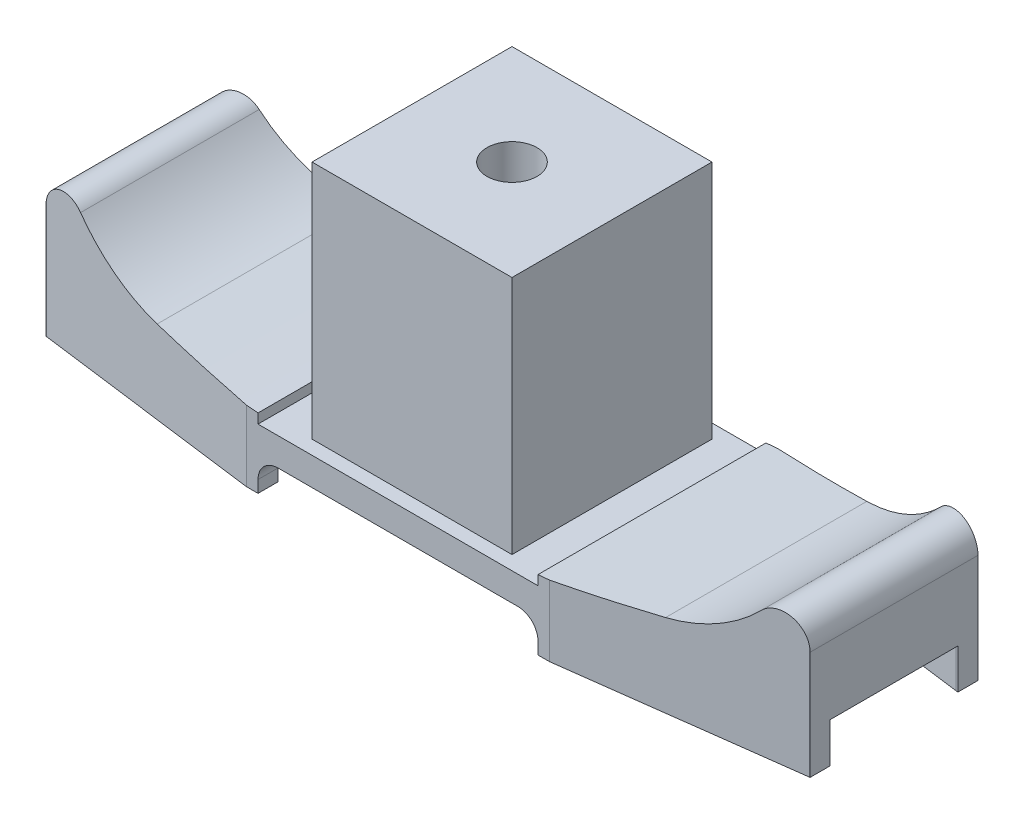
SolidWorks part; units mm, degrees
material "ABS"
ref_plane "Front Plane" through (0, 0, 0) normal (0, 0, 1) x (1, 0, 0)
ref_plane "Top Plane" through (0, 0, 0) normal (0, 1, 0) x (1, 0, 0)
ref_plane "Right Plane" through (0, 0, 0) normal (1, 0, 0) x (0, 0, -1)
sketch "Sketch1" plane through (0, 0, 0) normal (0, 1, 0) x (1, 0, 0)
  line L0 (-7.5767, 5.7) -> (-19.5345, 4.1659)
  line L1 (-7.5779, -5.7) -> (-19.0844, -4.1992)
  line L2 (7.5779, -5.7) -> (-7.5779, -5.7)
  line L3 (7.5779, -5.7) -> (19.0844, -4.1992)
  line L4 (7.5779, 5.7) -> (19.0844, 4.1992)
  line L5 (-15, 0) -> (15, 0) construction
  line L6 (15, 0) -> (19, 0) construction
  line L7 (0, 0) -> (0, 4.5) construction
  line L8 (22, 0) -> (22, 4.5) construction
  line L9 (-7.5, 4.5) -> (7.5, 4.5)
  line L10 (19, 0) -> (22, 0) construction
  line L11 (7.5, 4.5) -> (19, 3)
  line L12 (7.5, 4.5) -> (7.5, -4.5) construction
  line L13 (7.5, -4.5) -> (-7.5, -4.5)
  line L14 (7.5, -4.5) -> (19, -3)
  line L15 (-7.5, -4.5) -> (-19, -3)
  line L16 (-7.5, 4.5) -> (-7.5, -4.5) construction
  line L17 (-19, 0) -> (-22, 0) construction
  line L18 (-15, 0) -> (-19, 0) construction
  line L19 (-7.5, 4.5) -> (-19.3818, 2.9756)
  line L20 (-7.5767, 5.7) -> (7.5779, 5.7)
  line L21 (-7.513, -4.7) -> (-19.0132, -3.2)
  line L22 (-7.5128, 4.7) -> (-19.4072, 3.174)
  line L23 (-7.5128, 4.7) -> (7.513, 4.7)
  line L24 (7.513, 4.7) -> (19.0132, 3.2)
  line L25 (7.513, -4.7) -> (19.0132, -3.2)
  line L26 (7.513, -4.7) -> (-7.513, -4.7)
  circle A0 centre (19, 0) radius 1.5
  circle A1 centre (15, 0) radius 1.5
  arc A2 (19, -3) -> (19, 3) centre (19, 0) ccw
  circle A3 centre (9.5, 0) radius 2
  circle A4 centre (-9.5, 0) radius 2
  arc A5 (-19, -3) -> (-19.3818, 2.9756) centre (-19, 0) cw
  circle A6 centre (-15, 0) radius 1.5
  circle A7 centre (-19, 0) radius 1.5
  circle A8 centre (0, 0) radius 1.5
  arc A9 (-19.0844, -4.1992) -> (-19.5345, 4.1659) centre (-19, 0) cw
  arc A10 (19.0844, -4.1992) -> (19.0844, 4.1992) centre (19, 0) ccw
  arc A11 (-19.0132, -3.2) -> (-19.4072, 3.174) centre (-19, 0) cw
  arc A12 (19.0132, -3.2) -> (19.0132, 3.2) centre (19, 0) ccw
  point P25 (0, -4.5)
  dimension "D1" = 3
  dimension "D2" = 3
  dimension "D3" = 4
  dimension "D4" = 4
  dimension "D5" = 3
  dimension "D6" = 3
  dimension "D7" = 3
  dimension "D8" = 3
  dimension "D9" = 44
  dimension "D10" = 15
  dimension "D11" = 30
  dimension "D12" = 0.2
extrude "Boss-Extrude1" add sketch "Sketch1" along normal blind 2 contours L3 A10 L4 L20 L0 A9 L1 L2 L15 A5 L19 L9 L11 A2 L14 L13
sketch "Sketch2" plane through (0, 2, 0) normal (0, 1, 0) x (1, 0, 0)
  line L6 (7.5779, -5.7) -> (19.0844, -4.1992)
  line L7 (19.0844, 4.1992) -> (7.5779, 5.7)
  line L8 (7.5779, 5.7) -> (-7.5767, 5.7)
  line L9 (-7.5767, 5.7) -> (-19.5345, 4.1659)
  line L10 (-19.0844, -4.1992) -> (-7.5779, -5.7)
  line L11 (-7.5779, -5.7) -> (7.5779, -5.7)
  line L12 (7.5779, -5.7) -> (19.0844, -4.1992)
  line L13 (19.0844, 4.1992) -> (7.5779, 5.7)
  line L14 (7.5779, 5.7) -> (-7.5767, 5.7)
  line L15 (-7.5767, 5.7) -> (-19.5345, 4.1659)
  line L16 (-19.0844, -4.1992) -> (-7.5779, -5.7)
  line L17 (-7.5779, -5.7) -> (7.5779, -5.7)
  arc A2 (19.0844, -4.1992) -> (19.0844, 4.1992) centre (19, 0) ccw
  arc A3 (-19.5345, 4.1659) -> (-19.0844, -4.1992) centre (-19, 0) ccw
  arc A4 (19.0844, -4.1992) -> (19.0844, 4.1992) centre (19, 0) ccw
  arc A5 (-19.5345, 4.1659) -> (-19.0844, -4.1992) centre (-19, 0) ccw
  dimension "D1" = 0
extrude "Boss-Extrude2" add sketch "Sketch2" along normal blind 1
sketch "Sketch3" plane through (0, 3, 0) normal (0, 1, 0) x (1, 0, 0)
  line L0 (-5, 0) -> (-5, 5)
  line L1 (-5, 5) -> (5, 5)
  line L2 (5, 5) -> (5, -5)
  line L3 (5, -5) -> (-5, -5)
  line L4 (-5, -5) -> (-5, 0)
  circle A0 centre (0, 0) radius 5 construction
  dimension "D1" = 10
extrude "Boss-Extrude3" add sketch "Sketch3" along normal blind 12
sketch "Sketch4" plane through (0, 0, 5.7) normal (0, 0, 1) x (1, 0, 0)
  line L0 (-7.5779, 3) -> (7.5779, 3) construction
  line L1 (-7.5779, 3) -> (7.5779, 3)
  line L2 (-7, 4) -> (7, 4)
  line L3 (0, 0) -> (0, 89.2)
  line L4 (-10.4945, 18.9799) -> (-12.7116, 4.1446)
  line L5 (10.4945, 18.9799) -> (12.7116, 4.1446)
  line L6 (-19.103, 3) -> (-19.103, 11.5623)
  line L7 (-19.0844, 3) -> (-7.5779, 3) construction
  line L8 (19.103, 3) -> (19.103, 11.5623)
  line L9 (23.2, 3) -> (19.0844, 3) construction
  line L10 (-7, 3) -> (-7, 3.4854)
  line L11 (7, 3) -> (7, 3.4854)
  line L12 (-7, 3) -> (-19.103, 3)
  line L13 (-7.5779, 4) -> (7.5779, 4) construction
  line L14 (7.5779, 3) -> (19.103, 3)
  arc A0 (-12.7116, 4.1446) -> (12.7116, 4.1446) centre (0, 89.2) ccw
  circle A1 centre (0, 89.2) radius 71
  circle A2 centre (-11.603, 11.5623) radius 7.5
  circle A3 centre (11.603, 11.5623) radius 7.5
  arc A4 (19.103, 5.3485) -> (-19.103, 5.3485) centre (0, 89.2) ccw
  arc A5 (19.103, 5.421) -> (16.9496, 6.3026) centre (17.8459, 5.421) ccw
  arc A6 (-17.1173, 6.4787) -> (-19.103, 5.7031) centre (-17.9587, 5.7031) ccw
  arc A7 (-18.9592, 13.0239) -> (18.9592, 13.0239) centre (0, 89.2) ccw
  point P36 (0, 10.7)
  dimension "D2" = 172
  dimension "D5" = 142
  dimension "D8" = 78.5
  dimension "D3" = 8.5
  dimension "D4" = 8.5
  dimension "D6" = 7
  dimension "D7" = 7
  dimension "D9" = 7.7
  dimension "D1" = 1
extrude "Boss-Extrude4" add sketch "Sketch4" against normal up to surface (11.4 mm away)
sketch "Sketch5" plane through (0, 3, 0) normal (0, -1, 0) x (1, 0, 0)
  line L1 (19.103, 4.1987) -> (19.103, -4.1987)
  line L2 (-19.103, -4.2212) -> (-19.103, 4.1987)
  line L3 (-19.0844, 4.1992) -> (-7.5779, 5.7)
  line L4 (-7.5779, 5.7) -> (-19.103, 5.7)
  line L5 (-19.103, 5.7) -> (-19.103, 4.1987)
  line L6 (-19.0844, 4.1992) -> (-7.5779, 5.7)
  line L7 (-7.5779, 5.7) -> (-19.103, 5.7)
  line L8 (-19.103, 5.7) -> (-19.103, 4.1987)
  line L9 (19.103, 5.7) -> (7.5779, 5.7)
  line L10 (7.5779, 5.7) -> (19.0844, 4.1992)
  line L11 (19.103, 4.1987) -> (19.103, 5.7)
  line L12 (19.103, 5.7) -> (7.5779, 5.7)
  line L13 (7.5779, 5.7) -> (19.0844, 4.1992)
  line L14 (19.103, 4.1987) -> (19.103, 5.7)
  line L15 (-19.103, -5.7) -> (-7.5767, -5.7)
  line L16 (-7.5767, -5.7) -> (-19.103, -4.2212)
  line L17 (-19.103, -4.2212) -> (-19.103, -5.7)
  line L18 (-19.103, -5.7) -> (-7.5767, -5.7)
  line L19 (-7.5767, -5.7) -> (-19.103, -4.2212)
  line L20 (-19.103, -4.2212) -> (-19.103, -5.7)
  line L21 (19.103, -5.7) -> (19.103, -4.1987)
  line L22 (19.0844, -4.1992) -> (7.5779, -5.7)
  line L23 (7.5779, -5.7) -> (19.103, -5.7)
  line L24 (19.103, -5.7) -> (19.103, -4.1987)
  line L25 (19.0844, -4.1992) -> (7.5779, -5.7)
  line L26 (7.5779, -5.7) -> (19.103, -5.7)
  line L27 (-19.5345, -4.1659) -> (-19.103, -4.2212)
  line L28 (-19.103, -4.2212) -> (-19.103, 4.1987)
  line L29 (-19.5345, -4.1659) -> (-19.103, -4.2212)
  line L30 (19.103, 4.1987) -> (19.103, -4.1987)
  arc A1 (-19.0844, 4.1992) -> (-19.103, 4.1987) centre (-19, 0) ccw
  arc A2 (-19.0844, 4.1992) -> (-19.103, 4.1987) centre (-19, 0) ccw
  arc A3 (19.103, 4.1987) -> (19.0844, 4.1992) centre (19, 0) ccw
  arc A4 (19.103, 4.1987) -> (19.0844, 4.1992) centre (19, 0) ccw
  arc A5 (19.0844, -4.1992) -> (19.103, -4.1987) centre (19, 0) ccw
  arc A6 (19.0844, -4.1992) -> (19.103, -4.1987) centre (19, 0) ccw
  arc A7 (-19.103, 4.1987) -> (-19.5345, -4.1659) centre (-19, 0) ccw
  arc A8 (-19.103, 4.1987) -> (-19.5345, -4.1659) centre (-19, 0) ccw
  arc A9 (19.103, -4.1987) -> (19.103, 4.1987) centre (19, 0) ccw
  arc A10 (19.103, -4.1987) -> (19.103, 4.1987) centre (19, 0) ccw
  dimension "D1" = 0
  dimension "D2" = 0
  dimension "D3" = 0
  dimension "D4" = 0
  dimension "D5" = 0
  dimension "D6" = 0
extrude "Cut-Extrude1" cut sketch "Sketch5" against normal through all both and the other way through all contours A6 L25 L26 L24 | L19 L20 L18 | A4 L14 L12 L13 | L30 A10 | L28 A8 L29
sketch "Sketch6" plane through (0, 15, 0) normal (0, 1, 0) x (1, 0, 0)
  circle A0 centre (0, 0) radius 1.25
extrude "Cut-Extrude2" cut sketch "Sketch6" against normal through all
sketch "Sketch7" plane through (0, 0, -5.7) normal (0, 0, -1) x (-1, 0, 0)
  line L0 (-7, 0) -> (-7, 0.6)
  line L1 (7.5767, 0) -> (-7.5779, 0) construction
  line L2 (7, 0) -> (7, 0.6)
  line L3 (-6, 1.6) -> (6, 1.6)
  line L4 (7.5767, 0) -> (-7.5779, 0)
  arc A0 (7, 0.6) -> (6, 1.6) centre (6, 0.6) ccw
  arc A1 (-6, 1.6) -> (-7, 0.6) centre (-6, 0.6) ccw
  line M10 (-7.5779, 0) -> (7.5767, 0)
  dimension "D2" = 1
  dimension "D1" = 1.6
extrude "Cut-Extrude3" cut sketch "Sketch7" against normal through all contours L3 A1 L0 L2 A0 M10
